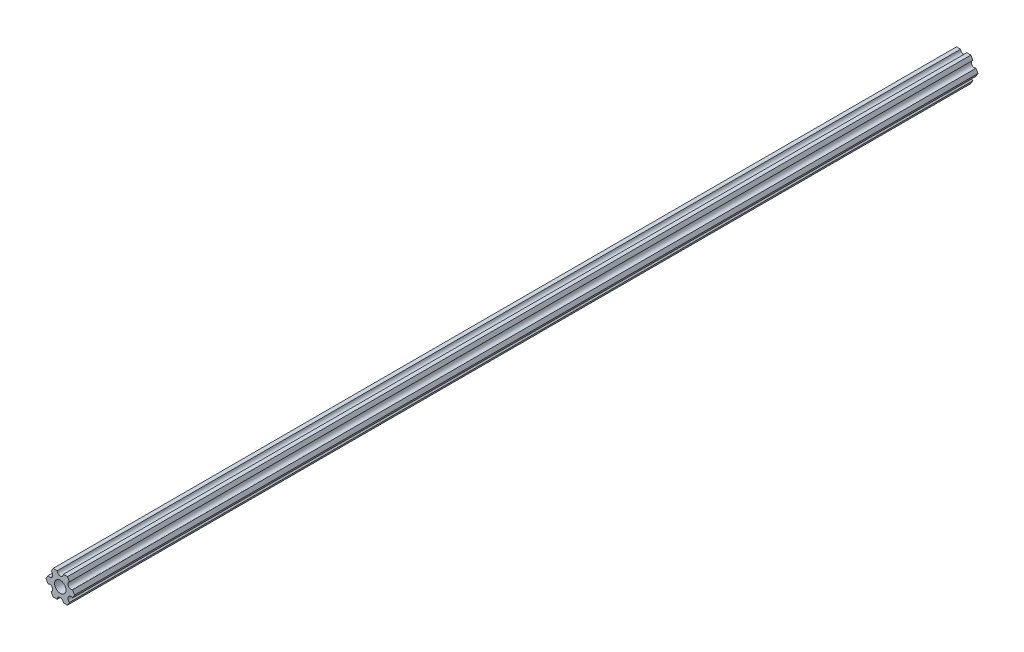
SolidWorks part; units mm, degrees
material "6061-T6 (SS)"
ref_plane "Front Plane" through (0, 0, 0) normal (0, 0, 1) x (1, 0, 0)
ref_plane "Top Plane" through (0, 0, 0) normal (0, 1, 0) x (1, 0, 0)
ref_plane "Right Plane" through (0, 0, 0) normal (1, 0, 0) x (0, 0, -1)
sketch "Sketch1" plane through (0, 0, 0) normal (0, 0, 1) x (1, 0, 0)
  line L0 (-4.7055, -4.5498) -> (-3.6662, -6.35)
  line L1 (-3.6662, -6.35) -> (-1.5875, -6.35)
  line L2 (1.5875, -6.35) -> (3.6662, -6.35)
  line L3 (3.6662, -6.35) -> (4.7055, -4.5498)
  line L4 (6.293, -1.8002) -> (7.3323, 0)
  line L5 (7.3323, 0) -> (6.293, 1.8002)
  line L6 (4.7055, 4.5498) -> (3.6662, 6.35)
  line L7 (3.6662, 6.35) -> (1.5875, 6.35)
  line L8 (-1.5875, 6.35) -> (-3.6662, 6.35)
  line L9 (-3.6662, 6.35) -> (-4.7055, 4.5498)
  line L10 (-6.293, 1.8002) -> (-7.3323, 0)
  line L11 (-7.3323, 0) -> (-6.293, -1.8002)
  circle A0 centre (0, 0) radius 2.9337
  arc A1 (-6.293, -1.8002) -> (-4.7055, -4.5498) centre (-5.4993, -3.175) cw
  arc A2 (-1.5875, -6.35) -> (1.5875, -6.35) centre (0, -6.35) cw
  arc A3 (4.7055, -4.5498) -> (6.293, -1.8002) centre (5.4993, -3.175) cw
  arc A4 (6.293, 1.8002) -> (4.7055, 4.5498) centre (5.4993, 3.175) cw
  arc A5 (1.5875, 6.35) -> (-1.5875, 6.35) centre (0, 6.35) cw
  arc A6 (-4.7055, 4.5498) -> (-6.293, 1.8002) centre (-5.4993, 3.175) cw
extrude "Boss-Extrude1" add sketch "Sketch1" against normal blind 463.55
